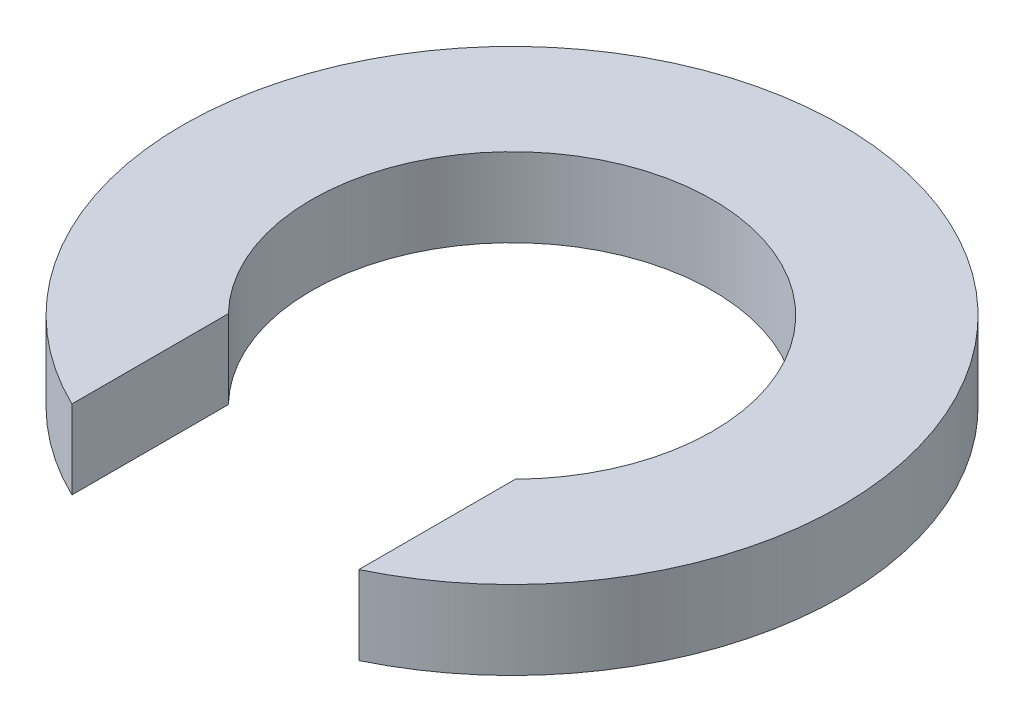
SolidWorks part; units mm, degrees
ref_plane "Alzado" through (0, 0, 0) normal (0, 0, 1) x (1, 0, 0)
ref_plane "Planta" through (0, 0, 0) normal (0, 1, 0) x (1, 0, 0)
ref_plane "Vista lateral" through (0, 0, 0) normal (1, 0, 0) x (0, 0, -1)
sketch "Croquis1" plane through (0, 0, 0) normal (0, 1, 0) x (1, 0, 0)
  circle A2 centre (0, 0) radius 11.5
  circle A3 centre (0, 0) radius 7
  dimension "D1" = 23
  dimension "D2" = 14
extrude "Saliente-Extruir1" add sketch "Croquis1" along normal blind 2.75
sketch "Croquis2" plane through (0, 2.75, 0) normal (0, 1, 0) x (1, 0, 0)
  line L0 (-5.0052, -4.8936) -> (-5.0052, -10.3536) construction
  line L1 (0, 11.5) -> (0, 0) construction
  line L2 (5.0052, -4.8936) -> (5.0052, -10.3536) construction
  line L4 (-5.0052, -4.8936) -> (5.0052, -4.8936)
  line L5 (-5.0052, -4.8936) -> (-5.0052, -11.5)
  line L6 (-5.0052, -11.5) -> (5.0052, -11.5)
  line L7 (5.0052, -4.8936) -> (5.0052, -11.5)
  circle A0 centre (0, 0) radius 7 construction
  circle A1 centre (0, 0) radius 11.5 construction
  dimension "D1" = 5.46
extrude "Cortar-Extruir1" cut sketch "Croquis2" against normal through all
